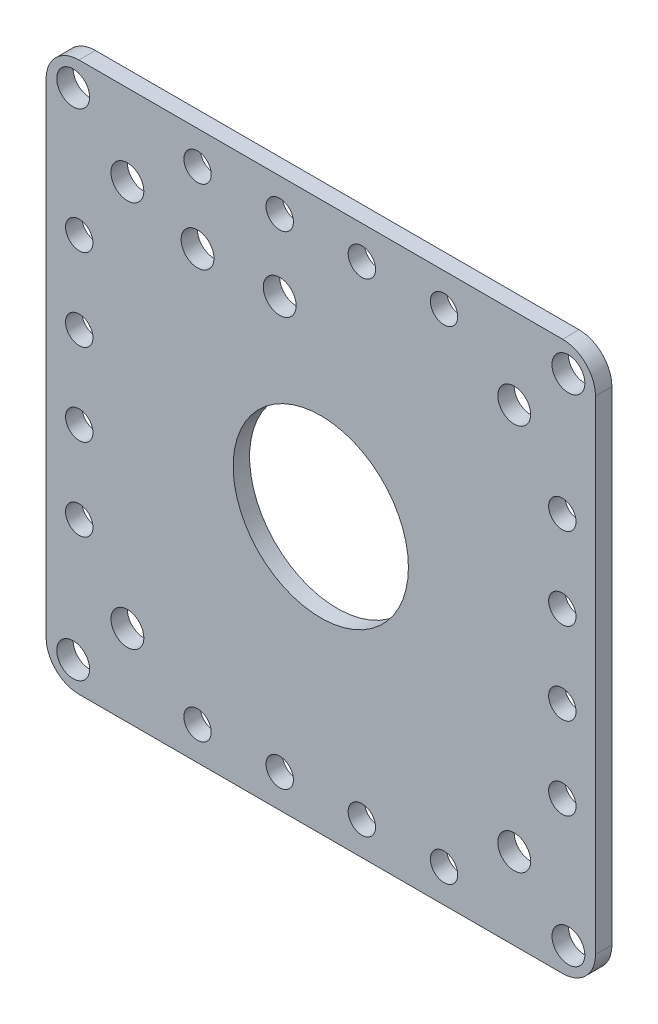
SolidWorks part; units mm, degrees
ref_plane "Front Plane" through (0, 0, 0) normal (0, 0, 1) x (1, 0, 0)
ref_plane "Top Plane" through (0, 0, 0) normal (0, 1, 0) x (1, 0, 0)
ref_plane "Right Plane" through (0, 0, 0) normal (1, 0, 0) x (0, 0, -1)
sketch "Sketch1" plane through (0, 0, 0) normal (0, 0, 1) x (1, 0, 0)
  line L0 (-24.1963, 24.1963) -> (24.1963, -24.1963) construction
  line L1 (-22.075, -25.075) -> (22.075, -25.075)
  line L2 (-25.075, -22.075) -> (-25.075, 22.075)
  line L3 (-22.075, 25.075) -> (22.075, 25.075)
  line L4 (25.075, -22.075) -> (25.075, 22.075)
  line L5 (-24.1963, -24.1963) -> (24.1963, 24.1963) construction
  line L6 (-25.075, 0) -> (25.075, 0) construction
  line L7 (0, 25.075) -> (0, -25.075) construction
  line L8 (0, 22.05) -> (-3.75, 22.05) construction
  line L9 (-11.25, 22.05) -> (-11.25, 15.55) construction
  circle A0 centre (0, 0) radius 8
  circle A1 centre (-22.6053, 22.6053) radius 1.5
  arc A2 (-22.075, -25.075) -> (-25.075, -22.075) centre (-22.075, -22.075) cw
  arc A3 (25.075, -22.075) -> (22.075, -25.075) centre (22.075, -22.075) cw
  arc A4 (22.075, 25.075) -> (25.075, 22.075) centre (22.075, 22.075) cw
  arc A5 (-22.075, 25.075) -> (-25.075, 22.075) centre (-22.075, 22.075) ccw
  circle A6 centre (22.6053, -22.6053) radius 1.5
  circle A7 centre (22.6053, 22.6053) radius 1.5
  circle A8 centre (-22.6053, -22.6053) radius 1.5
  circle A9 centre (-17.6556, 17.6556) radius 1.5
  circle A10 centre (17.6556, -17.6556) radius 1.5
  circle A11 centre (17.6556, 17.6556) radius 1.5
  circle A12 centre (-17.6556, -17.6556) radius 1.5
  circle A13 centre (-3.75, 22.05) radius 1.25
  circle A14 centre (3.75, 22.05) radius 1.25
  circle A15 centre (11.25, 22.05) radius 1.25
  circle A16 centre (-11.25, 22.05) radius 1.25
  circle A17 centre (11.25, -22.05) radius 1.25
  circle A18 centre (3.75, -22.05) radius 1.25
  circle A19 centre (-3.75, -22.05) radius 1.25
  circle A20 centre (-11.25, -22.05) radius 1.25
  circle A21 centre (-22.05, 3.75) radius 1.25
  circle A22 centre (-22.05, 11.25) radius 1.25
  circle A23 centre (-22.05, -11.25) radius 1.25
  circle A24 centre (-22.05, -3.75) radius 1.25
  circle A25 centre (22.05, -11.25) radius 1.25
  circle A26 centre (22.05, -3.75) radius 1.25
  circle A27 centre (22.05, 3.75) radius 1.25
  circle A28 centre (22.05, 11.25) radius 1.25
  circle A29 centre (-11.25, 15.55) radius 1.5
  circle A30 centre (-3.75, 15.55) radius 1.5
  point P0 (0, 0)
  dimension "D2" = 2.25
  dimension "D3" = 3
  dimension "D1" = 2.25
  dimension "D4" = 7
  dimension "D5" = 3.025
  dimension "D6" = 3
  dimension "D8" = 2
  dimension "D7" = 2
extrude "Boss-Extrude1" add sketch "Sketch1" along normal blind 1.5
